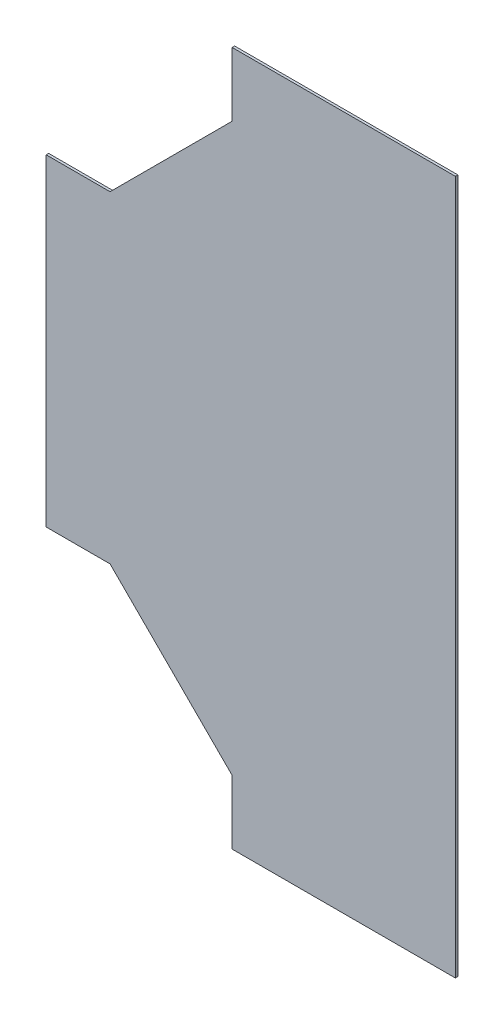
SolidWorks part; units mm, degrees
ref_plane "Front Plane" through (0, 0, 0) normal (1, 0, 0) x (0, 1, 0)
ref_plane "Top Plane" through (0, 0, 0) normal (0, 0, 1) x (0, 1, 0)
ref_plane "Right Plane" through (0, 0, 0) normal (0, 1, 0) x (-1, 0, 0)
sketch "Sketch1" plane through (0, 0, 0) normal (0, 0, 1) x (0, 1, 0)
  line L1 (-355.6, -209.55) -> (355.6, -209.55)
  line L2 (-355.6, -209.55) -> (-355.6, 209.55)
  line L3 (-355.6, 209.55) -> (355.6, 209.55)
  line L4 (355.6, -209.55) -> (355.6, 209.55)
  line L5 (-355.6, -209.55) -> (355.6, 209.55) construction
  line L6 (-355.6, 209.55) -> (355.6, -209.55) construction
  point P0 (0, 0)
  dimension "D1" = 711.2
  dimension "D2" = 419.1
extrude "Boss-Extrude1" add sketch "Sketch1" along normal blind 2.54
sketch "Sketch2" plane through (0, 0, 2.54) normal (0, 0, 1) x (1, 0, 0)
  line L0 (-209.55, 165.1) -> (-19.05, 165.1) construction
  line L1 (-209.55, 355.6) -> (-209.55, -355.6) construction
  line L2 (-19.05, 165.1) -> (-19.05, 355.6) construction
  line L3 (209.55, 355.6) -> (-209.55, 355.6) construction
  line L4 (-144.1127, 165.1) -> (-19.05, 290.1627)
  line L5 (-19.05, 355.6) -> (-19.05, 290.1627)
  line L6 (-144.1127, 165.1) -> (-209.55, 165.1)
  line L7 (-209.55, 0) -> (209.55, 0) construction
  line L8 (209.55, -355.6) -> (209.55, 355.6) construction
  line L9 (-19.05, 355.6) -> (-209.55, 355.6)
  line L10 (-209.55, 355.6) -> (-209.55, 165.1)
  line L11 (-19.05, -355.6) -> (-209.55, -355.6)
  line L12 (-19.05, -355.6) -> (-19.05, -290.1627)
  line L13 (-144.1127, -165.1) -> (-19.05, -290.1627)
  line L14 (-144.1127, -165.1) -> (-209.55, -165.1)
  line L15 (-209.55, -355.6) -> (-209.55, -165.1)
  dimension "D1" = 190.5
  dimension "D2" = 45
  dimension "D3" = 180.975
extrude "Cut-Extrude1" cut sketch "Sketch2" against normal through all
